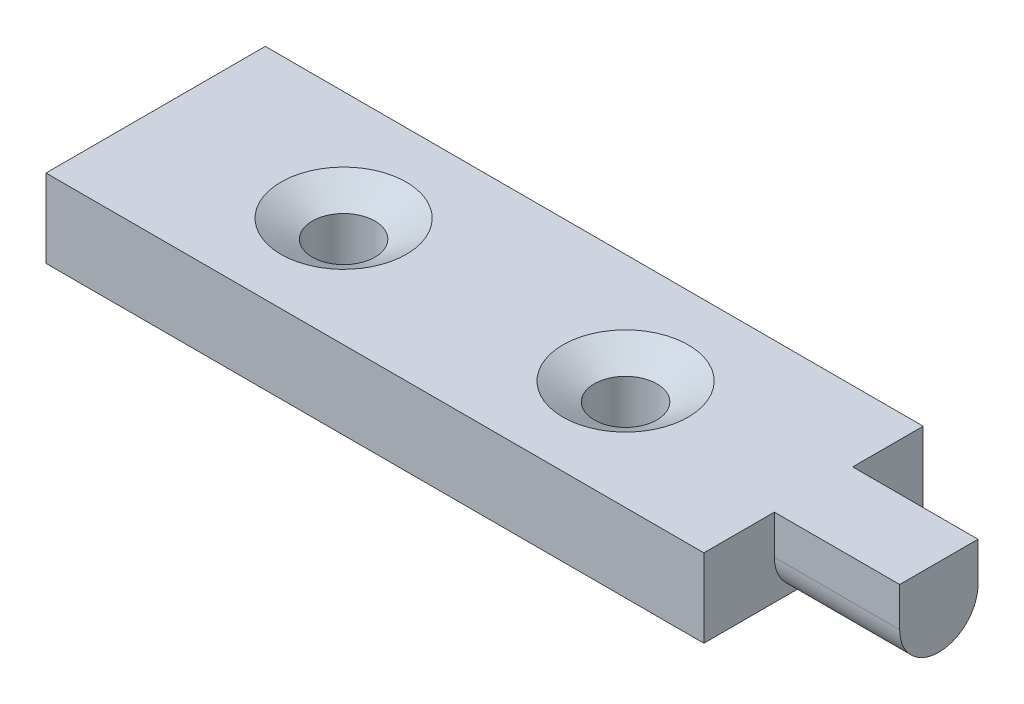
SolidWorks part; units mm, degrees
ref_plane "Front Plane" through (0, 0, 0) normal (0, 0, 1) x (1, 0, 0)
ref_plane "Top Plane" through (0, 0, 0) normal (0, 1, 0) x (1, 0, 0)
ref_plane "Right Plane" through (0, 0, 0) normal (1, 0, 0) x (0, 0, -1)
sketch "Sketch1" plane through (0, 0, 0) normal (0, 1, 0) x (1, 0, 0)
  line L0 (-24.0984, 1.7213) -> (25.9016, 1.7213) construction
  line L2 (-24.0984, 8.7213) -> (25.9016, 8.7213)
  line L3 (-24.0984, 8.7213) -> (-24.0984, -5.2787)
  line L4 (-24.0984, -5.2787) -> (25.9016, -5.2787)
  line L5 (25.9016, 8.7213) -> (25.9016, -5.2787)
  circle A0 centre (5.9016, 1.7213) radius 2
  circle A1 centre (-12.0984, 1.7213) radius 2
  dimension "D3" = 20
  dimension "D4" = 18
  dimension "D1" = 14
  dimension "D2" = 50
extrude "Boss-Extrude1" add sketch "Sketch1" along normal blind 5
sketch "Sketch2" plane through (25.9016, 0, 0) normal (1, 0, 0) x (0, 0, -1)
  line L0 (1.7213, 5) -> (1.7213, 0) construction
  line L1 (-5.2787, 5) -> (8.7213, 5) construction
  line L2 (-5.2787, 0) -> (8.7213, 0) construction
  line L3 (-5.2787, 2.5) -> (8.7213, 2.5) construction
  line L4 (-5.2787, 5) -> (-5.2787, 0) construction
  line L5 (8.7213, 5) -> (8.7213, 0) construction
  line L7 (-5.2787, 5) -> (8.7213, 5)
  line L8 (-5.2787, 5) -> (-5.2787, 0)
  line L9 (-5.2787, 0) -> (8.7213, 0)
  line L10 (8.7213, 5) -> (8.7213, 0)
  line L11 (-0.7787, 2.5) -> (4.2213, 2.5)
  line L12 (-0.7787, 2.5) -> (-0.7787, 5)
  line L13 (-0.7787, 5) -> (4.2213, 5)
  line L14 (4.2213, 2.5) -> (4.2213, 5)
  circle A0 centre (1.7213, 2.5) radius 2.5
  line M1 (-5.2787, 0) -> (8.7213, 0)
  line M2 (8.7213, 0) -> (8.7213, 5)
  line M3 (8.7213, 5) -> (-5.2787, 5)
  line M4 (-5.2787, 5) -> (-5.2787, 0)
extrude "Cut-Extrude1" cut sketch "Sketch2" against normal blind 8 contours A0 L7 M4 M1 | A0 L9 M2 M3
chamfer "Chamfer1" distance 2 angle 30 2 edges at (-12.0984, 5, 0.2787) (5.9016, 5, 0.2787)
